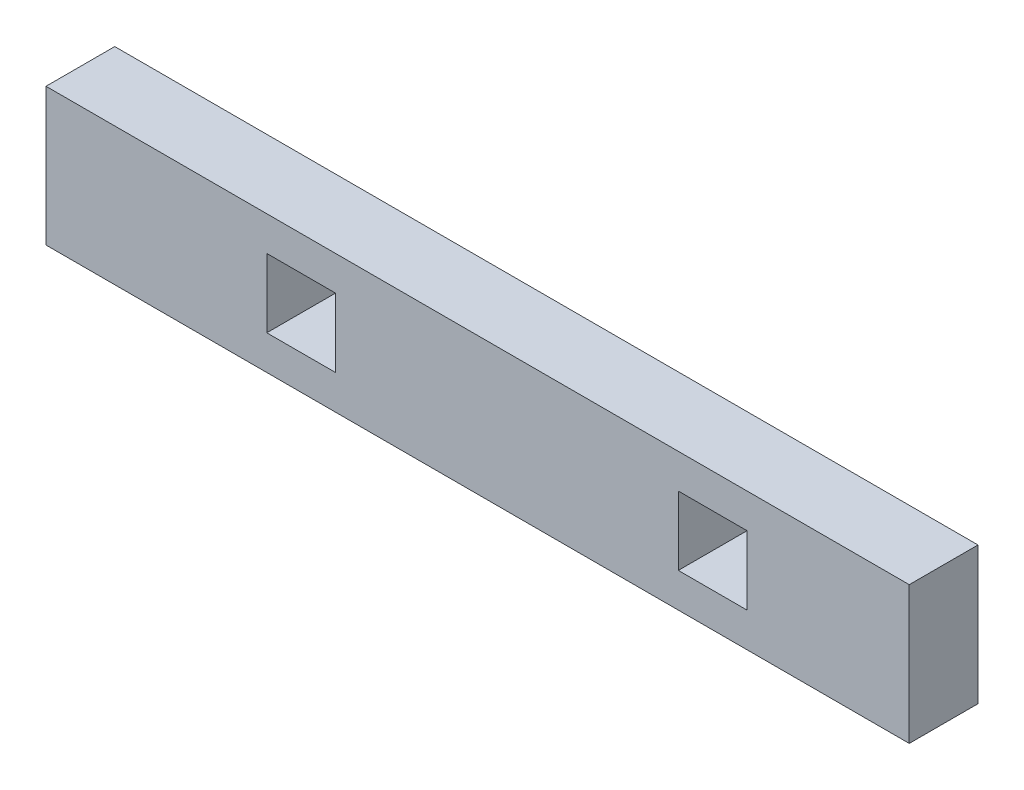
SolidWorks part; units mm, degrees
material "Balsa - Aero Experimental"
ref_plane "Front Plane" through (0, 0, 0) normal (0, 0, 1) x (1, 0, 0)
ref_plane "Top Plane" through (0, 0, 0) normal (0, 1, 0) x (1, 0, 0)
ref_plane "Right Plane" through (0, 0, 0) normal (1, 0, 0) x (0, 0, -1)
sketch "Sketch1" plane through (0, 0, 0) normal (0, 0, 1) x (1, 0, 0)
  line L0 (63.4388, 3.1705) -> (63.4388, -3.1795)
  line L1 (63.4388, -3.1795) -> (23.5766, -3.1795)
  line L2 (23.5766, -3.1795) -> (23.5766, 3.1705)
  line L3 (23.5766, 3.1705) -> (63.4388, 3.1705)
  line L4 (55.9498, -1.592) -> (55.9498, 1.583) construction
  line L5 (55.9498, 1.583) -> (55.9498, -1.592)
  line L6 (55.9498, -1.592) -> (52.7748, -1.592)
  line L7 (52.7748, -1.592) -> (52.7748, 1.583)
  line L8 (52.7748, 1.583) -> (55.9498, 1.583)
  line L9 (36.9459, 1.583) -> (33.7709, 1.583)
  line L10 (33.7709, 1.583) -> (33.7709, -1.592)
  line L11 (33.7709, -1.592) -> (36.9459, -1.592)
  line L12 (36.9459, -1.592) -> (36.9459, 1.583)
  spline S0 degree 3 poles (70.8207, 2.6565) (70.5662, 2.6753) (69.7939, 2.7318) (66.9503, 2.9365) (63.3246, 3.1826) (59.1794, 3.4402) (55.0332, 3.681) (50.8854, 3.8951) (46.7362, 4.0765) (43.6235, 4.1948) (40.5102, 4.2939) (37.3962, 4.371) (34.2817, 4.4228) (31.1669, 4.4472) (28.0519, 4.4388) (25.5218, 4.3999) (24.0302, 4.3628) (23.5766, 4.3501) knots 0 0 0 0 0.016189 0.049121 0.180849 0.246713 0.312577 0.444304 0.510168 0.576032 0.641896 0.70776 0.773624 0.839488 0.905352 0.971216 1 1 1 1 construction
  point P2 (63.4388, -0.0045)
  point P7 (55.9498, -0.0045)
  dimension "D1" = 6.35
extrude "Boss-Extrude1" add sketch "Sketch1" against normal up to surface (3.175 mm away)
